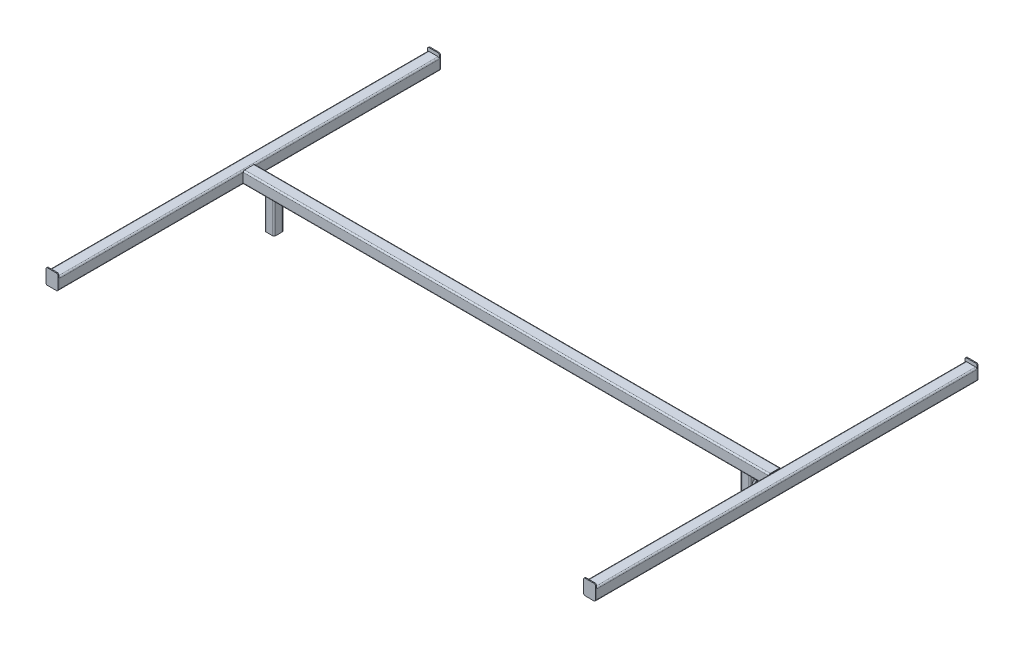
SolidWorks part; units mm, degrees
ref_plane "Спереди" through (0, 0, 0) normal (0, 0, 1) x (1, 0, 0)
ref_plane "Сверху" through (0, 0, 0) normal (0, 1, 0) x (1, 0, 0)
ref_plane "Справа" through (0, 0, 0) normal (1, 0, 0) x (0, 0, -1)
sketch "Эскиз1" plane through (0, 0, 0) normal (0, 1, 0) x (1, 0, 0)
  line L0 (-565, 0) -> (565, 0)
  line L1 (-565, 400) -> (-565, -400)
  line L2 (565, 400) -> (565, -400)
  dimension "D1" = 1130
  dimension "D2" = 800
sketch "Эскиз2" plane through (0, 0, 0) normal (0, 0, 1) x (1, 0, 0)
  line L0 (-500, 0) -> (-500, -77.5)
  line L1 (-565, 0) -> (565, 0) construction
  line L2 (500, 0) -> (500, -77.5)
  line L3 (0, 0) -> (0, -228.6421) construction
  dimension "D1" = 77.5
  dimension "1200" = 1000
other "Квадратная труба 2 X 2 X 0.25(1)"
ref_plane "Плоскость1" through (-565, 0, -400) normal (0, 0, 1) x (1, 0, 0)
sketch "Sketch1" plane through (-565, 0, -400) normal (0, 0, 1) x (1, 0, 0)
  line L0 (-9.5, -10.5) -> (9.5, -10.5)
  line L1 (-10.5, -9.5) -> (-10.5, 9.5)
  line L2 (9.5, 10.5) -> (-9.5, 10.5)
  line L3 (10.5, 9.5) -> (10.5, -9.5)
  line L4 (-9.5, -12.5) -> (9.5, -12.5)
  line L5 (-12.5, -9.5) -> (-12.5, 9.5)
  line L6 (9.5, 12.5) -> (-9.5, 12.5)
  line L7 (12.5, 9.5) -> (12.5, -9.5)
  line L8 (0, 0) -> (10.5, 0) construction
  line L9 (0, 0) -> (0, 10.5) construction
  arc A0 (12.5, 9.5) -> (9.5, 12.5) centre (9.5, 9.5) ccw
  arc A1 (9.5, -12.5) -> (12.5, -9.5) centre (9.5, -9.5) ccw
  arc A2 (-12.5, -9.5) -> (-9.5, -12.5) centre (-9.5, -9.5) ccw
  arc A3 (-9.5, 12.5) -> (-12.5, 9.5) centre (-9.5, 9.5) ccw
  arc A4 (-9.5, 10.5) -> (-10.5, 9.5) centre (-9.5, 9.5) ccw
  arc A5 (10.5, 9.5) -> (9.5, 10.5) centre (9.5, 9.5) ccw
  arc A6 (9.5, -10.5) -> (10.5, -9.5) centre (9.5, -9.5) ccw
  arc A7 (-10.5, -9.5) -> (-9.5, -10.5) centre (-9.5, -9.5) ccw
  point P3 (0, 12.5)
  point P4 (12.5, 0)
  point P5 (0, -12.5)
  point P6 (-12.5, 0)
  point P7 (-12.5, 12.5)
  point P8 (-12.5, -12.5)
  point P33 (0, 0)
  point P35 (12.5, -12.5)
  point P36 (12.5, 12.5)
  point P37 (0, 0)
  dimension "D1" = 3
  dimension "Thickness" = 2
  dimension "V_leg" = 25
other "Квадратная труба 2 X 2 X 0.25(2)"
ref_plane "Плоскость2" through (-500, 0, 0) normal (0, -1, 0) x (1, 0, 0)
sketch "Sketch11" plane through (-500, 0, 0) normal (0, -1, 0) x (1, 0, 0)
  line L0 (-7, -8.5) -> (7, -8.5)
  line L1 (-8.5, -7) -> (-8.5, 7)
  line L2 (7, 8.5) -> (-7, 8.5)
  line L3 (8.5, 7) -> (8.5, -7)
  line L4 (-7, -10) -> (7, -10)
  line L5 (-10, -7) -> (-10, 7)
  line L6 (7, 10) -> (-7, 10)
  line L7 (10, 7) -> (10, -7)
  line L8 (0, 0) -> (8.5, 0) construction
  line L9 (0, 0) -> (0, 8.5) construction
  arc A0 (10, 7) -> (7, 10) centre (7, 7) ccw
  arc A1 (7, -10) -> (10, -7) centre (7, -7) ccw
  arc A2 (-10, -7) -> (-7, -10) centre (-7, -7) ccw
  arc A3 (-7, 10) -> (-10, 7) centre (-7, 7) ccw
  arc A4 (-7, 8.5) -> (-8.5, 7) centre (-7, 7) ccw
  arc A5 (8.5, 7) -> (7, 8.5) centre (7, 7) ccw
  arc A6 (7, -8.5) -> (8.5, -7) centre (7, -7) ccw
  arc A7 (-8.5, -7) -> (-7, -8.5) centre (-7, -7) ccw
  point P3 (0, 10)
  point P4 (10, 0)
  point P5 (0, -10)
  point P6 (-10, 0)
  point P7 (-10, 10)
  point P8 (-10, -10)
  point P33 (0, 0)
  point P35 (10, -10)
  point P36 (10, 10)
  point P37 (0, 0)
  dimension "D1" = 3
  dimension "Thickness" = 1.5
  dimension "V_leg" = 20
other "Отсечь/Удлинить2"
sketch "Эскиз5" plane through (0, 0, 400) normal (0, 0, 1) x (1, 0, 0)
  line L0 (-574.5, 19.5) -> (-555.5, 19.5)
  line L1 (-555.5, 12.5) -> (-574.5, 12.5) construction
  line L4 (-555.5, 12.5) -> (-574.5, 12.5)
  line L5 (-577.5, 9.5) -> (-577.5, -9.5)
  line L6 (-574.5, -12.5) -> (-555.5, -12.5)
  line L7 (-552.5, -9.5) -> (-552.5, 9.5)
  line L9 (-577.5, 16.5) -> (-577.5, -9.5)
  line L10 (-574.5, -12.5) -> (-555.5, -12.5)
  line L11 (-552.5, -9.5) -> (-552.5, 16.5)
  arc A0 (-555.5, 19.5) -> (-552.5, 16.5) centre (-555.5, 16.5) cw
  arc A1 (-577.5, 16.5) -> (-574.5, 19.5) centre (-574.5, 16.5) cw
  arc A4 (-552.5, 9.5) -> (-555.5, 12.5) centre (-555.5, 9.5) ccw
  arc A5 (-574.5, 12.5) -> (-577.5, 9.5) centre (-574.5, 9.5) ccw
  arc A6 (-577.5, -9.5) -> (-574.5, -12.5) centre (-574.5, -9.5) ccw
  arc A7 (-555.5, -12.5) -> (-552.5, -9.5) centre (-555.5, -9.5) ccw
  arc A10 (-577.5, -9.5) -> (-574.5, -12.5) centre (-574.5, -9.5) ccw
  arc A11 (-555.5, -12.5) -> (-552.5, -9.5) centre (-555.5, -9.5) ccw
  dimension "D3" = 3
  dimension "D2" = 7
  dimension "D1" = 0
extrude "Бобышка-Вытянуть1" add sketch "Эскиз5" along normal blind 2 separate body
mirror "Зеркальное отражение2" about plane through (0, 0, 0) normal (1, 0, 0) of bodies 120
mirror "Зеркальное отражение3" about plane through (0, 0, 0) normal (0, 0, 1) of bodies 120 121
sketch "Эскиз7" plane through (510, 0, 0) normal (1, 0, 0) x (0, 0, -1)
  line L7 (5.3116, -29.5) -> (2.6558, -24.9)
  line L8 (2.6558, -24.9) -> (-2.6558, -24.9)
  line L9 (-2.6558, -24.9) -> (-5.3116, -29.5)
  line L10 (-5.3116, -29.5) -> (-2.6558, -34.1)
  line L11 (-2.6558, -34.1) -> (2.6558, -34.1)
  line L18 (5.3116, -59.5) -> (2.6558, -54.9)
  line L19 (2.6558, -54.9) -> (-2.6558, -54.9)
  line L20 (-2.6558, -54.9) -> (-5.3116, -59.5)
  line L21 (-5.3116, -59.5) -> (-2.6558, -64.1)
  line L22 (-2.6558, -64.1) -> (2.6558, -64.1)
  line L23 (2.6558, -64.1) -> (5.3116, -59.5)
  line L36 (2.6558, -34.1) -> (5.3116, -29.5)
  circle A0 centre (0, -29.5) radius 3.75 construction
  circle A1 centre (0, -29.5) radius 4.6 construction
  circle A2 centre (0, -59.5) radius 3.75 construction
  circle A3 centre (0, -59.5) radius 4.6 construction
  point P0 (0, -29.5)
  point P1 (0, -59.5)
  dimension "D1" = 9.2
  dimension "D2" = 9.2
extrude "Вырез-Вытянуть3" cut sketch "Эскиз7" against normal up to next (1.5 mm away)
sketch "Эскиз8" plane through (-510, 0, 0) normal (-1, 0, 0) x (0, 0, 1)
  line L1 (2.6558, -34.1) -> (5.3116, -29.5)
  line L2 (5.3116, -29.5) -> (2.6558, -24.9)
  line L3 (2.6558, -24.9) -> (-2.6558, -24.9)
  line L4 (-2.6558, -24.9) -> (-5.3116, -29.5)
  line L5 (-5.3116, -29.5) -> (-2.6558, -34.1)
  line L6 (2.6558, -64.1) -> (5.3116, -59.5)
  line L7 (-2.6558, -34.1) -> (2.6558, -34.1)
  line L8 (5.3116, -59.5) -> (2.6558, -54.9)
  line L9 (2.6558, -54.9) -> (-2.6558, -54.9)
  line L10 (-2.6558, -54.9) -> (-5.3116, -59.5)
  line L11 (-5.3116, -59.5) -> (-2.6558, -64.1)
  line L12 (-2.6558, -64.1) -> (2.6558, -64.1)
  circle A0 centre (0, -29.5) radius 3.75 construction
  circle A1 centre (0, -29.5) radius 4.6 construction
  circle A2 centre (0, -59.5) radius 3.75 construction
  circle A3 centre (0, -59.5) radius 4.6 construction
  point P0 (0, -29.5)
  point P1 (0, -59.5)
  dimension "D1" = 9.2
  dimension "D2" = 9.2
extrude "Вырез-Вытянуть4" cut sketch "Эскиз8" against normal up to next (1.5 mm away)
equation "\"шестигранная зинковка\"=9.2"
equation "\"D1@Эскиз7\"=\"шестигранная зинковка\""
equation "\"D2@Эскиз7\"=\"шестигранная зинковка\""
equation "\"D2@Эскиз8\"=\"шестигранная зинковка\""
